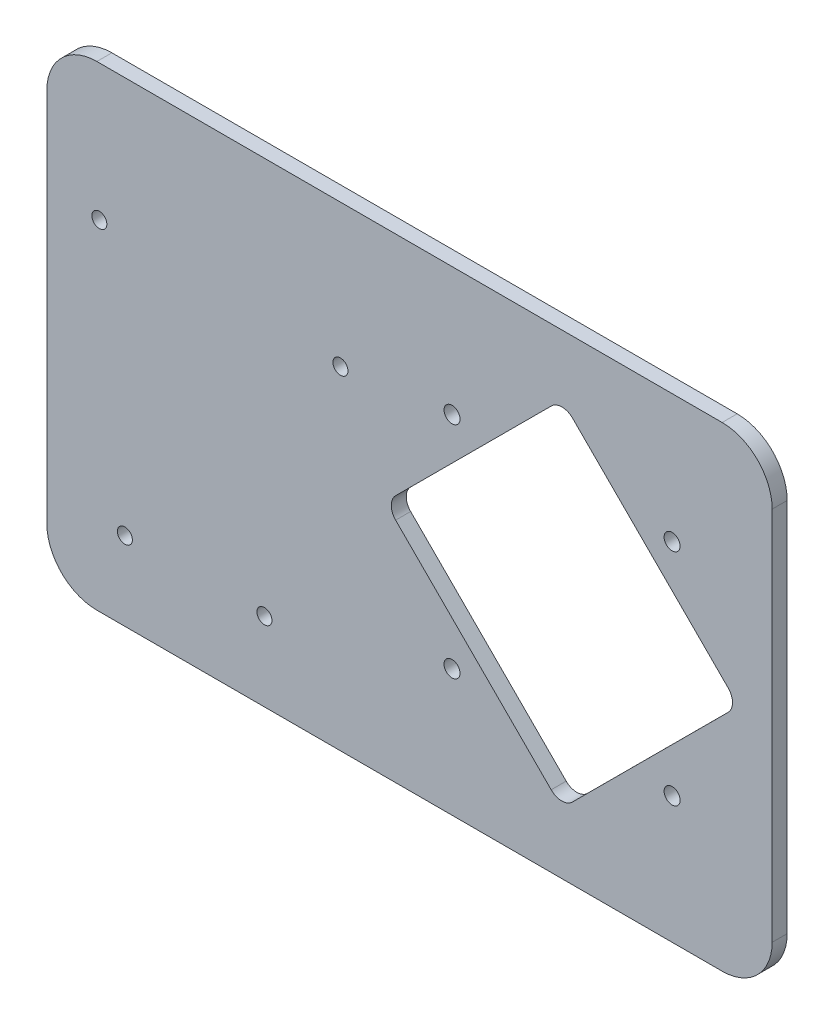
SolidWorks part; units mm, degrees
ref_plane "前视基准面" through (0, 0, 0) normal (0, 0, 1) x (1, 0, 0)
ref_plane "上视基准面" through (0, 0, 0) normal (0, 1, 0) x (1, 0, 0)
ref_plane "右视基准面" through (0, 0, 0) normal (1, 0, 0) x (0, 0, -1)
ref_plane "基准面4" through (0, 0, 0) normal (0, 0, -1) x (-1, 0, 0)
sketch "草图1" plane through (0, 0, 0) normal (0, 0, -1) x (-1, 0, 0)
  line L0 (-269.068, 2.3137) -> (-144.068, 2.3137)
  line L1 (-134.068, 12.3137) -> (-134.068, 87.313)
  line L2 (-144.068, 97.313) -> (-269.068, 97.313)
  line L3 (-279.068, 87.313) -> (-279.068, 12.3137)
  line L4 (-270.2662, 51.9692) -> (-239.1723, 83.1003)
  line L5 (-234.9297, 83.1028) -> (-203.7984, 52.0086)
  line L6 (-203.7958, 47.766) -> (-234.8898, 16.6349)
  line L7 (-239.1324, 16.6324) -> (-270.2637, 47.7266)
  arc A0 (-144.068, 2.3137) -> (-134.068, 12.3137) centre (-144.068, 12.3137) ccw
  arc A1 (-134.068, 87.313) -> (-144.068, 97.313) centre (-144.068, 87.313) ccw
  arc A2 (-269.068, 97.313) -> (-279.068, 87.313) centre (-269.068, 87.313) ccw
  arc A3 (-279.068, 12.3137) -> (-269.068, 2.3137) centre (-269.068, 12.3137) ccw
  circle A4 centre (-144.568, 70.1283) radius 1.5
  circle A5 centre (-192.767, 68.829) radius 1.5
  circle A6 centre (-149.668, 18.0288) radius 1.5
  circle A7 centre (-215.068, 71.6897) radius 1.5
  circle A8 centre (-259.067, 71.6897) radius 1.5
  circle A9 centre (-259.067, 27.6889) radius 1.5
  circle A10 centre (-215.068, 27.6889) radius 1.5
  circle A11 centre (-177.568, 18.0288) radius 1.5
  arc A12 (-239.1723, 83.1003) -> (-234.9297, 83.1028) centre (-237.0497, 80.9802) cw
  arc A13 (-203.7984, 52.0086) -> (-203.7958, 47.766) centre (-205.9184, 49.886) cw
  arc A14 (-234.8898, 16.6349) -> (-239.1324, 16.6324) centre (-237.0124, 18.755) cw
  arc A15 (-270.2637, 47.7266) -> (-270.2662, 51.9692) centre (-268.1437, 49.8492) cw
extrude "凸台-拉伸1" add sketch "草图1" against normal blind 3
sketch "草图2" plane through (0, 0, 3) normal (0, 0, 1) x (1, 0, 0)
  circle A0 centre (259.067, 71.6897) radius 1.6
  circle A1 centre (215.068, 71.6897) radius 1.6
  circle A2 centre (215.068, 27.6889) radius 1.6
  circle A3 centre (259.067, 27.6889) radius 1.6
  dimension "D1" = 3.2
extrude "切除-拉伸1" cut sketch "草图2" against normal through all
